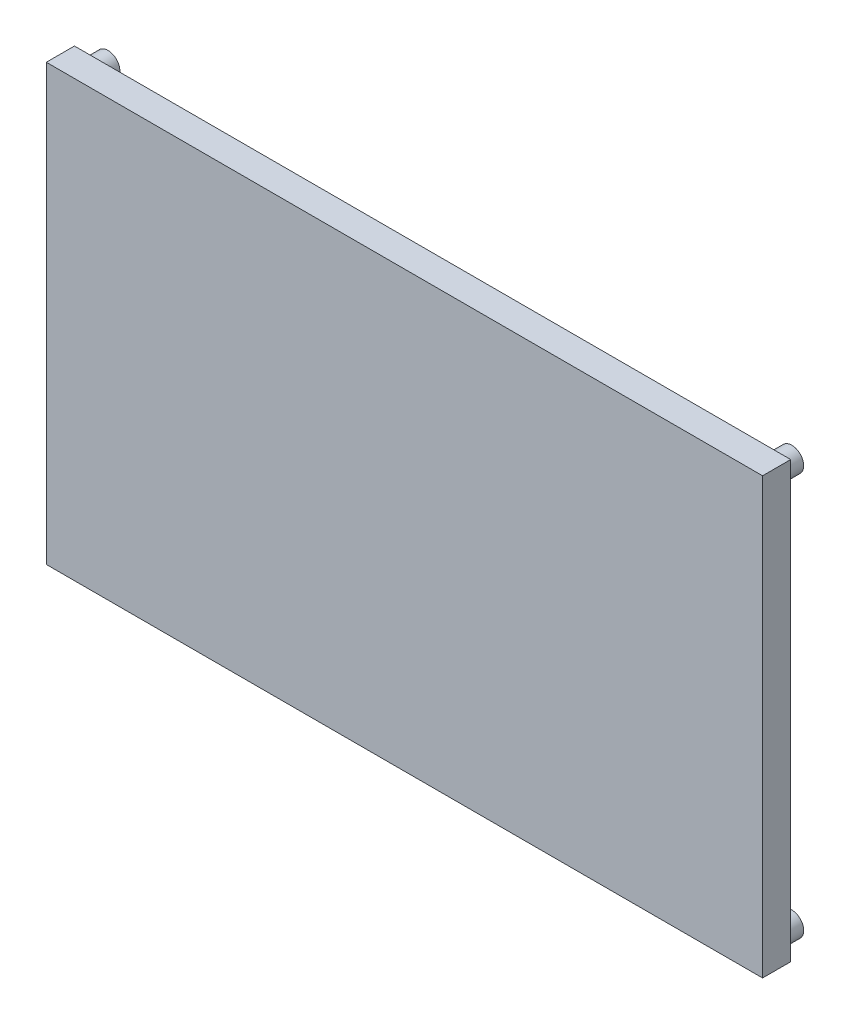
SolidWorks part; units mm, degrees
material "硅"
ref_plane "前视基准面" through (0, 0, 0) normal (0, 0, 1) x (1, 0, 0)
ref_plane "上视基准面" through (0, 0, 0) normal (0, 1, 0) x (1, 0, 0)
ref_plane "右视基准面" through (0, 0, 0) normal (1, 0, 0) x (0, 0, -1)
other "Configuration Table"
sketch "草图1" plane through (0, 0, 0) normal (0, 0, 1) x (1, 0, 0)
  line L1 (-82.75, -50.25) -> (82.75, -50.25)
  line L2 (-82.75, -50.25) -> (-82.75, 50.25)
  line L3 (-82.75, 50.25) -> (82.75, 50.25)
  line L4 (82.75, -50.25) -> (82.75, 50.25)
  line L5 (-82.75, -50.25) -> (82.75, 50.25) construction
  line L6 (-82.75, 50.25) -> (82.75, -50.25) construction
  point P0 (0, 0)
  dimension "D1" = 100.5
  dimension "D2" = 165.5
extrude "凸台-拉伸1" add sketch "草图1" along normal mid plane 6.5
sketch "草图2" plane through (0, 0, -3.25) normal (0, 0, -1) x (-1, 0, 0)
  line L0 (82.75, 50.25) -> (82.75, -50.25) construction
  line L1 (-82.75, 50.25) -> (82.75, 50.25) construction
  circle A0 centre (79, 46.5) radius 2.75
  dimension "D1" = 5.5
  dimension "D2" = 3.75
  dimension "D3" = 3.75
extrude "凸台-拉伸2" add sketch "草图2" along normal blind 4
mirror "镜向1" about plane through (0, 0, 0) normal (0, 1, 0) of "凸台-拉伸2" second plane through (0, 0, 0) second plane normal (1, 0, 0)
